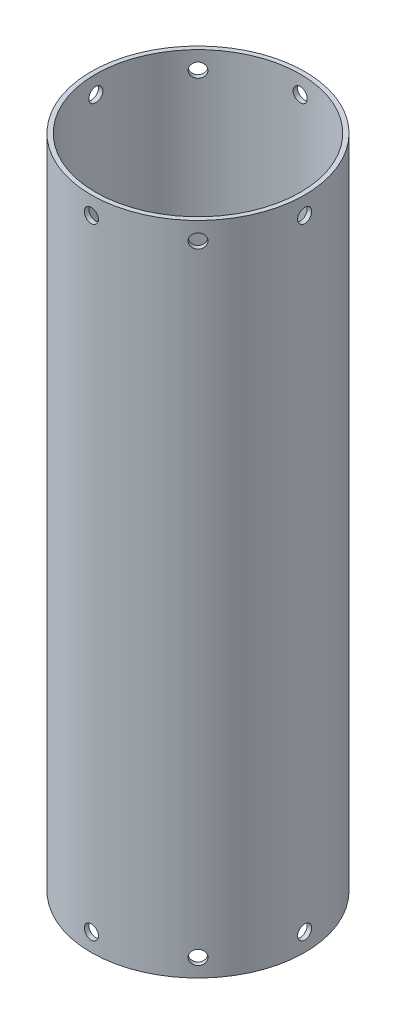
SolidWorks part; units mm, degrees
material "6061-T6 (SS)"
ref_plane "Front Plane" through (0, 0, 0) normal (0, 0, 1) x (1, 0, 0)
ref_plane "Top Plane" through (0, 0, 0) normal (0, 1, 0) x (1, 0, 0)
ref_plane "Right Plane" through (0, 0, 0) normal (1, 0, 0) x (0, 0, -1)
sketch "Sketch1" plane through (0, 0, 0) normal (0, 1, 0) x (1, 0, 0)
  circle A0 centre (0, 0) radius 76.2
  circle A1 centre (0, 0) radius 73.025
  dimension "D1" = 152.4
  dimension "D2" = 3.175
extrude "Boss-Extrude1" add sketch "Sketch1" along normal blind 467.995
sketch "Sketch2" [suppressed] plane through (0, 667.7406, 0) normal (1, 0, 0) x (0, 0, 1)
  circle A0 centre (0, -12.7) radius 4.7625 construction
  circle A1 centre (0, -12.7) radius 4.7625 construction
  circle A2 centre (0, -12.7) radius 5.0165
  dimension "D1" = 0.254
extrude "LOX Top Holes" [suppressed] cut sketch "Sketch2" along normal up to surface (76.0347 mm away) contours A2
pattern_circular "CirPattern1" [suppressed] count 8 over 360
sketch "Sketch3" [suppressed] plane through (0, 25.4, 0) normal (1, 0, 0) x (0, 0, -1)
  circle A0 centre (0, -12.7) radius 4.7625 construction
  circle A1 centre (0, -12.7) radius 4.7625 construction
  circle A2 centre (0, -12.7) radius 5.0165
  dimension "D1" = 0.254
extrude "LOX Bottom Holes" [suppressed] cut sketch "Sketch3" along normal up to surface (76.0347 mm away) contours A2
pattern_circular "CirPattern2" [suppressed] count 8 over 360
sketch "Sketch4" plane through (0, 442.595, 0) normal (1, 0, 0) x (0, 0, 1)
  circle A0 centre (0, -12.7) radius 4.7625 construction
  circle A1 centre (0, -12.7) radius 4.7625 construction
  circle A2 centre (0, -12.7) radius 5.0165
  dimension "D1" = 0.254
extrude "Cut-Extrude1" cut sketch "Sketch4" along normal up to surface (76.0347 mm away) contours A2
pattern_circular "CirPattern3" count 8 over 360 about axis through (0, 467.995, 0) along (0, 1, 0) of "Cut-Extrude1"
sketch "Sketch7" plane through (0, 25.4, 0) normal (1, 0, 0) x (0, 0, -1)
  circle A0 centre (0, -12.7) radius 4.7625 construction
  circle A1 centre (0, -12.7) radius 4.7625 construction
  circle A2 centre (0, -12.7) radius 5.0165
  dimension "D1" = 0.254
extrude "Cut-Extrude2" cut sketch "Sketch7" along normal up to surface (76.0347 mm away)
pattern_circular "CirPattern4" count 8 over 360 about axis through (0, 0, 0) along (0, 1, 0) of "Cut-Extrude2"
